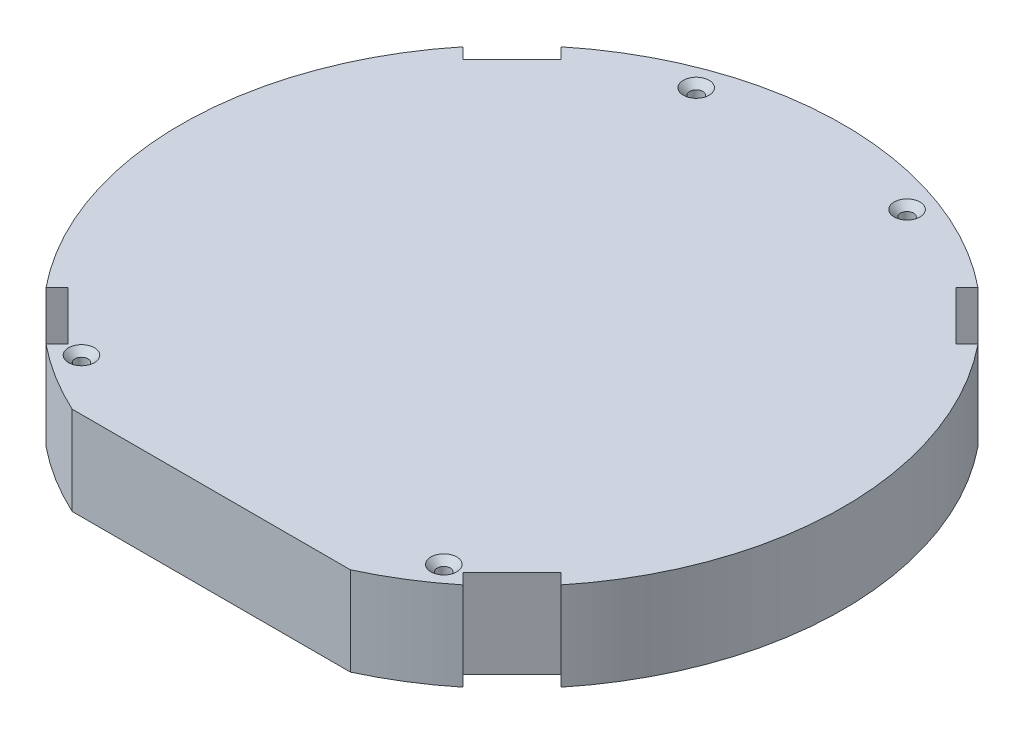
SolidWorks part; units mm, degrees
ref_plane "Plano frontal" through (0, 0, 0) normal (0, 0, 1) x (1, 0, 0)
ref_plane "Plano superior" through (0, 0, 0) normal (0, 1, 0) x (1, 0, 0)
ref_plane "Plano direito" through (0, 0, 0) normal (1, 0, 0) x (0, 0, -1)
sketch "Esboço1" plane through (0, 0, 0) normal (0, 1, 0) x (1, 0, 0)
  line L1 (36.1, -78.0563) -> (-36.1, -78.0563)
  line L2 (0, -78.0563) -> (0, 153.958) construction
  line L3 (60.4773, 60.4773) -> (-60.4773, -60.4773) construction
  line L4 (-66.8412, -54.1133) -> (-54.1133, -66.8412)
  line L5 (-66.8412, 54.1133) -> (-54.1133, 66.8412)
  line L6 (66.8412, -54.1133) -> (54.1133, -66.8412)
  line L7 (66.8412, 54.1133) -> (54.1133, 66.8412)
  line L8 (-60.4773, 60.4773) -> (60.4773, -60.4773) construction
  arc A0 (36.1, -78.0563) -> (54.1133, -66.8412) centre (0, 0) ccw
  arc A1 (-54.1133, -66.8412) -> (-36.1, -78.0563) centre (0, 0) ccw
  arc A2 (66.8412, -54.1133) -> (66.8412, 54.1133) centre (0, 0) ccw
  arc A3 (54.1133, 66.8412) -> (-54.1133, 66.8412) centre (0, 0) ccw
  arc A4 (-66.8412, 54.1133) -> (-66.8412, -54.1133) centre (0, 0) ccw
  point P8 (0, -78.0563)
  point P14 (-60.4773, -60.4773)
  point P17 (-60.4773, 60.4773)
  dimension "D1" = 172
  dimension "D2" = 36.1
  dimension "D3" = 45
  dimension "D4" = 45
  dimension "D5" = 9
  dimension "D6" = 9
extrude "Ressalto-extrusão1" add sketch "Esboço1" along normal blind 23
hole_wizard "Escareado para SFHCS M31" positions "Esboço5" profile "Esboço3" countersink size "M3" standard "Ansi Metric" end condition through all
sketch "Esboço5" plane through (0, 23, 0) normal (0, 1, 0) x (1, 0, 0)
  line L0 (0, 0) -> (0, 47.8911) construction
  line L2 (27.3616, 75.1754) -> (0, 0) construction
  line L3 (0, 0) -> (47.0228, -64.7214) construction
  point P0 (47.0228, -64.7214)
  point P2 (27.3616, 75.1754)
  point P20 (-47.0228, -64.7214)
  point P21 (-27.3616, 75.1754)
  dimension "D1" = 20
  dimension "D2" = 36
  dimension "D3" = 80
  dimension "D4" = 80
sketch "Esboço3" plane through (47.0228, 23, 64.7214) normal (1, 0, 0) x (0, 0, 1)
  line L0 (0, 0) -> (0, 23)
  line L1 (0, 23) -> (1.7, 23)
  line L2 (1.7, 23) -> (1.7, 1.66)
  line L3 (1.7, 1.66) -> (3.36, 0)
  line L5 (3.36, 0) -> (0, 0)
  line L6 (-1.7, 1.66) -> (-3.36, 0) construction
  line L11 (0, -6.35) -> (0, 107.95) construction
  dimension "Thru Hole Dia." = 3.4
  dimension "Thru Hole Depth" = 23
  dimension "Near C'Sink Dia." = 6.72
  dimension "Near C'Sink Angle" = 90
sketch "Esboço6" plane through (0, 23, 0) normal (0, 1, 0) x (1, 0, 0)
  line L0 (-66.8412, -54.1133) -> (-64.0128, -51.2849)
  line L1 (-64.0128, -51.2849) -> (-51.2849, -64.0128)
  line L2 (-51.2849, -64.0128) -> (-54.1133, -66.8412)
  line L3 (-66.8412, -54.1133) -> (-54.1133, -66.8412)
  line L4 (0, 0) -> (0, -35.0667) construction
  line L5 (0, 0) -> (-77.7489, 0) construction
  line L6 (-66.8412, 54.1133) -> (-64.0128, 51.2849)
  line L7 (-64.0128, 51.2849) -> (-51.2849, 64.0128)
  line L8 (-51.2849, 64.0128) -> (-54.1133, 66.8412)
  line L9 (-66.8412, 54.1133) -> (-54.1133, 66.8412)
  line L10 (66.8412, -54.1133) -> (64.0128, -51.2849)
  line L11 (64.0128, -51.2849) -> (51.2849, -64.0128)
  line L12 (51.2849, -64.0128) -> (54.1133, -66.8412)
  line L13 (66.8412, -54.1133) -> (54.1133, -66.8412)
  line L14 (66.8412, 54.1133) -> (54.1133, 66.8412)
  line L15 (51.2849, 64.0128) -> (54.1133, 66.8412)
  line L16 (64.0128, 51.2849) -> (51.2849, 64.0128)
  line L17 (66.8412, 54.1133) -> (64.0128, 51.2849)
  dimension "D1" = 4
extrude "Corte-extrusão1" cut sketch "Esboço6" against normal through all
